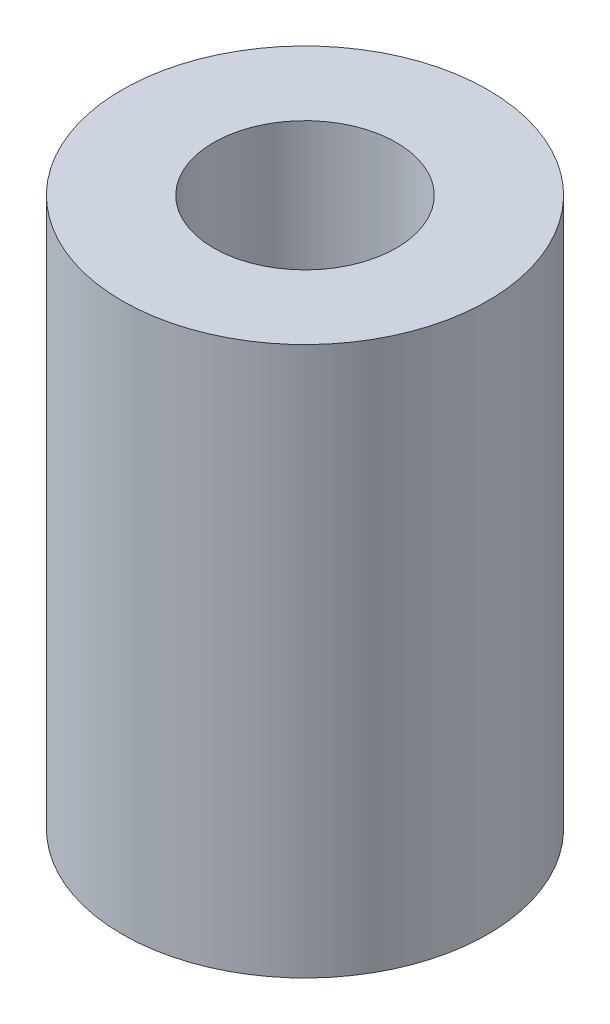
SolidWorks part; units mm, degrees
ref_plane "Front Plane" through (0, 0, 0) normal (0, 0, 1) x (1, 0, 0)
ref_plane "Top Plane" through (0, 0, 0) normal (0, 1, 0) x (1, 0, 0)
ref_plane "Right Plane" through (0, 0, 0) normal (1, 0, 0) x (0, 0, -1)
sketch "Sketch1" plane through (0, 0, 0) normal (0, 1, 0) x (1, 0, 0)
  circle A0 centre (0, 0) radius 5
  circle A1 centre (0, 0) radius 2.5
  dimension "D1" = 10
  dimension "D2" = 5
extrude "Boss-Extrude1" add sketch "Sketch1" along normal blind 15
